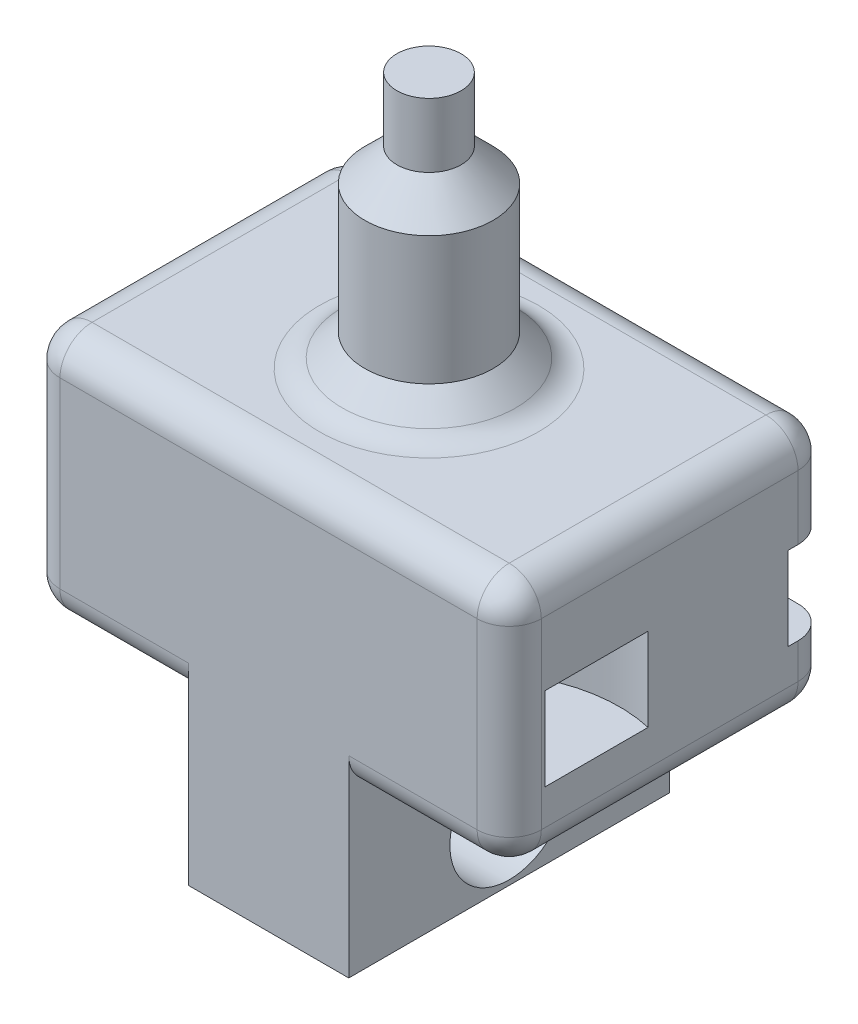
SolidWorks part; units mm, degrees
ref_plane "Plano frontal" through (0, 0, 0) normal (0, 0, 1) x (1, 0, 0)
ref_plane "Plano superior" through (0, 0, 0) normal (0, 1, 0) x (1, 0, 0)
ref_plane "Plano direito" through (0, 0, 0) normal (1, 0, 0) x (0, 0, -1)
sketch "Esboço2" plane through (0, 0, 0) normal (1, 0, 0) x (0, 0, -1)
  line L0 (0, 0) -> (100, 0)
  line L1 (100, 0) -> (100, 60)
  line L2 (100, 60) -> (0, 60)
  line L3 (0, 60) -> (0, 0)
  line L4 (0, 60) -> (0, 130)
  line L5 (0, 130) -> (100, 130)
  line L6 (100, 130) -> (100, 60)
  dimension "D1" = 100
  dimension "D2" = 60
  dimension "D3" = 70
extrude "Ressalto-extrusão1" add sketch "Esboço2" along normal blind 50 contours L2 L3 L0 L1
sketch "Esboço3" plane through (0, 0, 0) normal (-1, 0, 0) x (0, 0, 1)
  line L0 (-100, 60) -> (-100, 136.9663)
  line L1 (-100, 136.9663) -> (0, 136.9663)
  line L2 (0, 136.9663) -> (0, 60)
  line L3 (0, 60) -> (-100, 60)
extrude "Ressalto-extrusão2" add sketch "Esboço3" against normal blind 100 and the other way blind 50
sketch "Esboço4" plane through (0, 136.9663, 0) normal (0, 1, 0) x (1, 0, 0)
  line L0 (-50, 0) -> (-50, 100) construction
  line L2 (-50, 100) -> (100, 100) construction
  circle A0 centre (25, 50) radius 20
  dimension "D1" = 40
  dimension "D2" = 75
  dimension "D3" = 50
extrude "Ressalto-extrusão3" add sketch "Esboço4" along normal blind 60
fillet "Filete1" radius 10 14 edges at (-25, 60, -100) (75, 60, -100) (100, 60, -50) (-25, 60, 0) (75, 60, 0) (100, 98.4832, 0) (100, 98.4832, -100) (-50, 60, -50) (-50, 98.4832, 0) (-50, 98.4832, -100) (-50, 136.9663, -50) (25, 136.9663, -100) (100, 136.9663, -50) (25, 136.9663, 0)
chamfer "Chanfro1" distance 10 angle 45 1 edges at (25, 136.9663, -70)
sketch "Esboço6" plane through (50, 0, 0) normal (1, 0, 0) x (0, 0, -1)
  line L0 (0, 70) -> (0, 0) construction
  line L2 (90, 60) -> (10, 60) construction
  circle A0 centre (50, 30) radius 18.5
  dimension "D1" = 37
  dimension "D2" = 50
  dimension "D3" = 30
extrude "Corte-extrusão1" cut sketch "Esboço6" against normal through all
sketch "Esboço7" plane through (0, 0, -100) normal (0, 0, -1) x (-1, 0, 0)
  line L1 (-50, 0) -> (0, 0) construction
  line L2 (-50, 0) -> (-50, 70) construction
  line L4 (-90, 126.9663) -> (-90, 70) construction
  line L6 (40, 70) -> (40, 126.9663) construction
  circle A0 centre (-25, 35) radius 14.0828
  circle A1 centre (15, 99.9476) radius 15.3757
  circle A2 centre (-65, 99.9476) radius 15.3757
  point P15 (40, 98.4832)
  dimension "D1" = 35
  dimension "D2" = 25
  dimension "D3" = 25
  dimension "D4" = 25
extrude "Corte-extrusão2" cut sketch "Esboço7" against normal blind 27
sketch "Esboço8" plane through (0, 196.9663, 0) normal (0, 1, 0) x (1, 0, 0)
  circle A0 centre (25, 50) radius 10
extrude "Ressalto-extrusão4" add sketch "Esboço8" along normal blind 20
fillet "Filete2" radius 10 1 edges at (25, 136.9663, -80)
chamfer "Chanfro2" distance 10 angle 45 4 edges at (25, 0, -100) (0, 0, -50) (50, 0, -50) (25, 0, 0)
sketch "Esboço10" plane through (0, 0, 0) normal (0, 0, 1) x (1, 0, 0)
  line L0 (90, 70) -> (90, 126.9663) construction
  line L1 (-25, 106.9663) -> (2.5876, 106.9663)
  line L2 (-25, 106.9663) -> (-25, 81)
  line L3 (-25, 81) -> (2.5876, 81)
  line L4 (2.5876, 106.9663) -> (2.5876, 81)
  line L5 (45.5876, 81) -> (75, 81)
  line L6 (45.5876, 81) -> (45.5876, 106.9663)
  line L7 (45.5876, 106.9663) -> (75, 106.9663)
  line L8 (75, 81) -> (75, 106.9663)
  line L9 (-40, 126.9663) -> (-40, 70) construction
  line L10 (90, 126.9663) -> (-40, 126.9663) construction
  line L12 (50, 70) -> (90, 70) construction
  line L13 (-40, 70) -> (0, 70) construction
  dimension "D1" = 15
  dimension "D2" = 15
  dimension "D3" = 20
  dimension "D4" = 20
  dimension "D5" = 43
  dimension "D6" = 11
  dimension "D7" = 11
revolve "Corte-Revolução1" cut sketch "Esboço10" angle 325 about axis through (90, 136.9663, 0) along (0, 1, 0)
